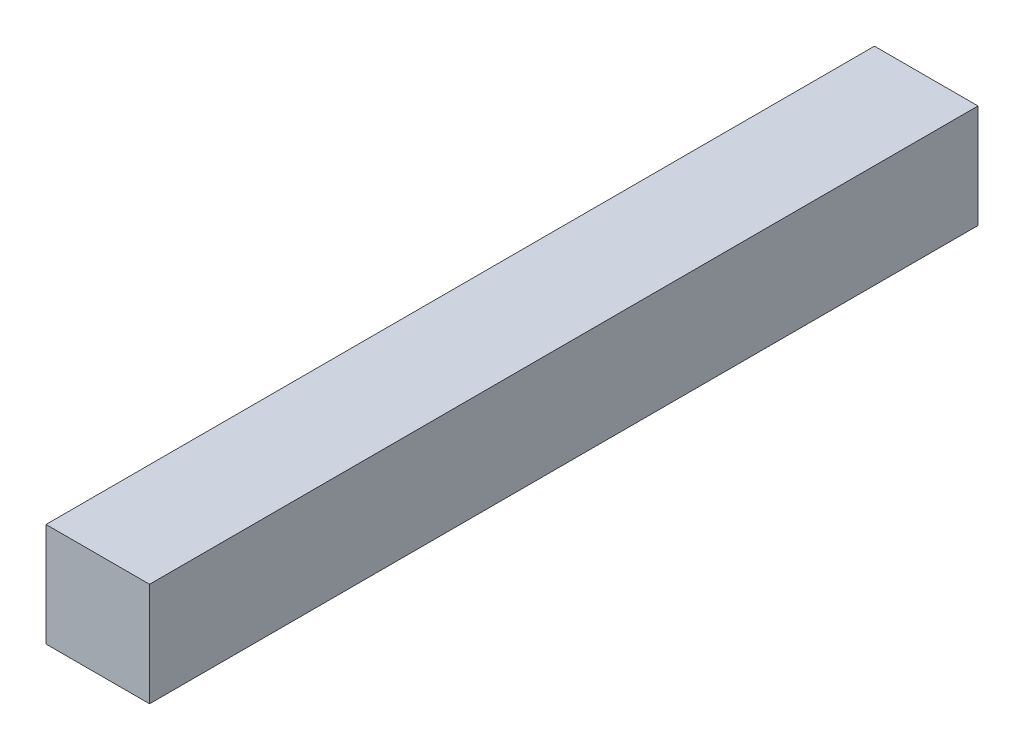
SolidWorks part; units mm, degrees
material "AISI 1045 Steel, cold drawn"
ref_plane "Front Plane" through (0, 0, 0) normal (0, 0, 1) x (1, 0, 0)
ref_plane "Top Plane" through (0, 0, 0) normal (0, 1, 0) x (1, 0, 0)
ref_plane "Right Plane" through (0, 0, 0) normal (1, 0, 0) x (0, 0, -1)
sketch "Sketch1" plane through (0, 0, 0) normal (0, 0, 1) x (1, 0, 0)
  line L1 (-1.5875, -1.5875) -> (1.5875, -1.5875)
  line L2 (-1.5875, -1.5875) -> (-1.5875, 1.5875)
  line L3 (-1.5875, 1.5875) -> (1.5875, 1.5875)
  line L4 (1.5875, -1.5875) -> (1.5875, 1.5875)
  line L5 (-1.5875, -1.5875) -> (1.5875, 1.5875) construction
  line L6 (-1.5875, 1.5875) -> (1.5875, -1.5875) construction
  point P0 (0, 0)
  dimension "D1" = 3.175
  dimension "D2" = 3.175
extrude "Boss-Extrude1" add sketch "Sketch1" along normal blind 25.4
